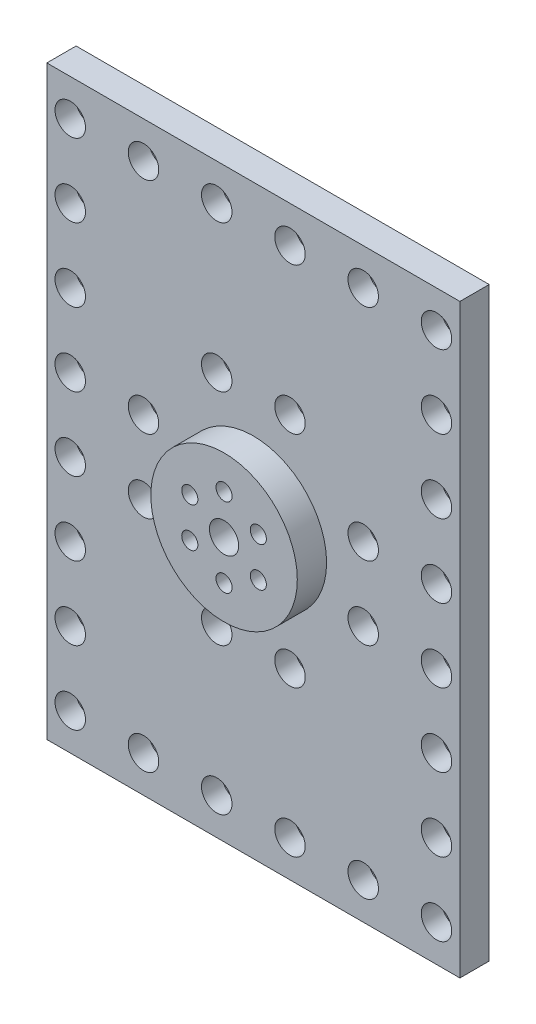
SolidWorks part; units mm, degrees
material "1060 합금"
ref_plane "정면" through (0, 0, 0) normal (0, 0, 1) x (1, 0, 0)
ref_plane "윗면" through (0, 0, 0) normal (0, 1, 0) x (1, 0, 0)
ref_plane "우측면" through (0, 0, 0) normal (1, 0, 0) x (0, 0, -1)
sketch "스케치1" plane through (0, 0, 0) normal (0, 0, 1) x (1, 0, 0)
  line L1 (0, 0) -> (-141, 0)
  line L2 (0, 0) -> (0, 200)
  line L3 (0, 200) -> (-141, 200)
  line L4 (-141, 0) -> (-141, 200)
  dimension "D1" = 141
  dimension "D2" = 200
extrude "보스-돌출1" add sketch "스케치1" along normal blind 10
sketch "스케치5" plane through (0, 0, 0) normal (0, 0, 1) x (1, 0, 0)
  line L0 (-70.5, 200) -> (-70.5, 0) construction
  line L1 (0, 200) -> (-141, 200) construction
  line L2 (-141, 0) -> (0, 0) construction
  line L3 (-141, 100) -> (0, 100) construction
  line L4 (-141, 200) -> (-141, 0) construction
  line L5 (0, 0) -> (0, 200) construction
  circle A0 centre (-70.5, 100) radius 13.5 construction
  circle A1 centre (-70.5, 100) radius 5
  circle A2 centre (-70.5, 113.5) radius 2.75
  circle A3 centre (-58.8087, 106.75) radius 2.75
  circle A4 centre (-58.8087, 93.25) radius 2.75
  circle A5 centre (-70.5, 86.5) radius 2.75
  circle A6 centre (-82.1913, 93.25) radius 2.75
  circle A7 centre (-82.1913, 106.75) radius 2.75
  point P29 (-70.5, 100)
  dimension "D1" = 27
  dimension "D2" = 10
  dimension "D3" = 5.5
  dimension "D4" = 6
extrude "컷-돌출5" cut sketch "스케치5" along direction (0, 0, 1) on the side of the normal through all
sketch "스케치6" plane through (0, 0, 0) normal (0, 0, -1) x (-1, 0, 0)
  circle A0 centre (70.5, 113.5) radius 5
  circle A1 centre (82.1913, 106.75) radius 5
  circle A2 centre (82.1913, 93.25) radius 5
  circle A3 centre (70.5, 86.5) radius 5
  circle A4 centre (58.8087, 93.25) radius 5
  circle A5 centre (58.8087, 106.75) radius 5
  dimension "D1" = 10
extrude "컷-돌출6" cut sketch "스케치6" against normal blind 5
sketch "스케치7" plane through (0, 0, 10) normal (0, 0, 1) x (1, 0, 0)
  circle A0 centre (-70.5, 100) radius 25
extrude "보스-돌출2" add sketch "스케치7" along normal blind 10
sketch "스케치8" plane through (0, 0, 10) normal (0, 0, -1) x (-1, 0, 0)
  circle A0 centre (82.1913, 106.75) radius 2.75
  circle A1 centre (82.1913, 93.25) radius 2.75
  circle A2 centre (70.5, 86.5) radius 2.75
  circle A3 centre (58.8087, 93.25) radius 2.75
  circle A4 centre (58.8087, 106.75) radius 2.75
  circle A5 centre (70.5, 113.5) radius 2.75
  circle A6 centre (70.5, 100) radius 5
extrude "컷-돌출7" cut sketch "스케치8" against normal blind 10
sketch "스케치9" plane through (0, 0, 10) normal (0, 0, 1) x (1, 0, 0)
  line L0 (0, 200) -> (-141, 200) construction
  line L1 (0, 0) -> (0, 200) construction
  circle A0 centre (-8, 187.5) radius 3.2
  circle A1 centre (-8, 12.5) radius 3.2
  circle A2 centre (-133, 187.5) radius 3.2
  circle A3 centre (-133, 12.5) radius 3.2
  circle A4 centre (-33, 187.5) radius 3.2
  circle A5 centre (-58, 187.5) radius 3.2
  circle A6 centre (-83, 187.5) radius 3.2
  circle A7 centre (-108, 187.5) radius 3.2
  circle A8 centre (-8, 162.5) radius 3.2
  circle A9 centre (-8, 137.5) radius 3.2
  circle A10 centre (-8, 112.5) radius 3.2
  circle A11 centre (-8, 87.5) radius 3.2
  circle A12 centre (-8, 62.5) radius 3.2
  circle A13 centre (-8, 37.5) radius 3.2
  circle A14 centre (-133, 162.5) radius 3.2
  circle A15 centre (-133, 137.5) radius 3.2
  circle A16 centre (-133, 112.5) radius 3.2
  circle A17 centre (-133, 87.5) radius 3.2
  circle A18 centre (-133, 62.5) radius 3.2
  circle A19 centre (-133, 37.5) radius 3.2
  circle A20 centre (-108, 12.5) radius 3.2
  circle A21 centre (-83, 12.5) radius 3.2
  circle A22 centre (-58, 12.5) radius 3.2
  circle A23 centre (-33, 12.5) radius 3.2
  circle A24 centre (-33, 112.5) radius 3.2
  circle A25 centre (-33, 87.5) radius 3.2
  circle A26 centre (-108, 112.5) radius 3.2
  circle A27 centre (-108, 87.5) radius 3.2
  circle A28 centre (-58, 137.5) radius 3.2
  circle A29 centre (-83, 137.5) radius 3.2
  circle A30 centre (-58, 62.5) radius 3.2
  circle A31 centre (-83, 62.5) radius 3.2
  dimension "D1" = 125
  dimension "D2" = 125
  dimension "D3" = 175
  dimension "D4" = 12.5
  dimension "D5" = 8
  dimension "D6" = 5
  dimension "D7" = 7
  dimension "D8" = 7
  dimension "D9" = 5
extrude "컷-돌출8" cut sketch "스케치9" against normal blind 50
sketch "스케치10" plane through (0, 0, 10) normal (0, 0, 1) x (1, 0, 0)
  circle A0 centre (-8, 187.5) radius 5.2
  circle A1 centre (-33, 187.5) radius 5.2
  circle A2 centre (-58, 187.5) radius 5.2
  circle A3 centre (-83, 187.5) radius 5.2
  circle A4 centre (-108, 187.5) radius 5.2
  circle A5 centre (-133, 187.5) radius 5.2
  circle A6 centre (-8, 162.5) radius 5.2
  circle A7 centre (-8, 137.5) radius 5.2
  circle A8 centre (-8, 112.5) radius 5.2
  circle A9 centre (-8, 87.5) radius 5.2
  circle A10 centre (-8, 62.5) radius 5.2
  circle A11 centre (-8, 37.5) radius 5.2
  circle A12 centre (-8, 12.5) radius 5.2
  circle A13 centre (-33, 12.5) radius 5.2
  circle A14 centre (-58, 12.5) radius 5.2
  circle A15 centre (-83, 12.5) radius 5.2
  circle A16 centre (-108, 12.5) radius 5.2
  circle A17 centre (-133, 12.5) radius 5.2
  circle A18 centre (-133, 162.5) radius 5.2
  circle A19 centre (-133, 137.5) radius 5.2
  circle A20 centre (-133, 112.5) radius 5.2
  circle A21 centre (-133, 87.5) radius 5.2
  circle A22 centre (-133, 62.5) radius 5.2
  circle A23 centre (-133, 37.5) radius 5.2
  circle A24 centre (-33, 112.5) radius 5.2
  circle A25 centre (-33, 87.5) radius 5.2
  circle A26 centre (-58, 62.5) radius 5.2
  circle A27 centre (-83, 62.5) radius 5.2
  circle A28 centre (-108, 87.5) radius 5.2
  circle A29 centre (-108, 112.5) radius 5.2
  circle A30 centre (-83, 137.5) radius 5.2
  circle A31 centre (-58, 137.5) radius 5.2
  dimension "D1" = 6
  dimension "D2" = 8
  dimension "D3" = 6
  dimension "D4" = 7
extrude "컷-돌출9" cut sketch "스케치10" against normal blind 7
